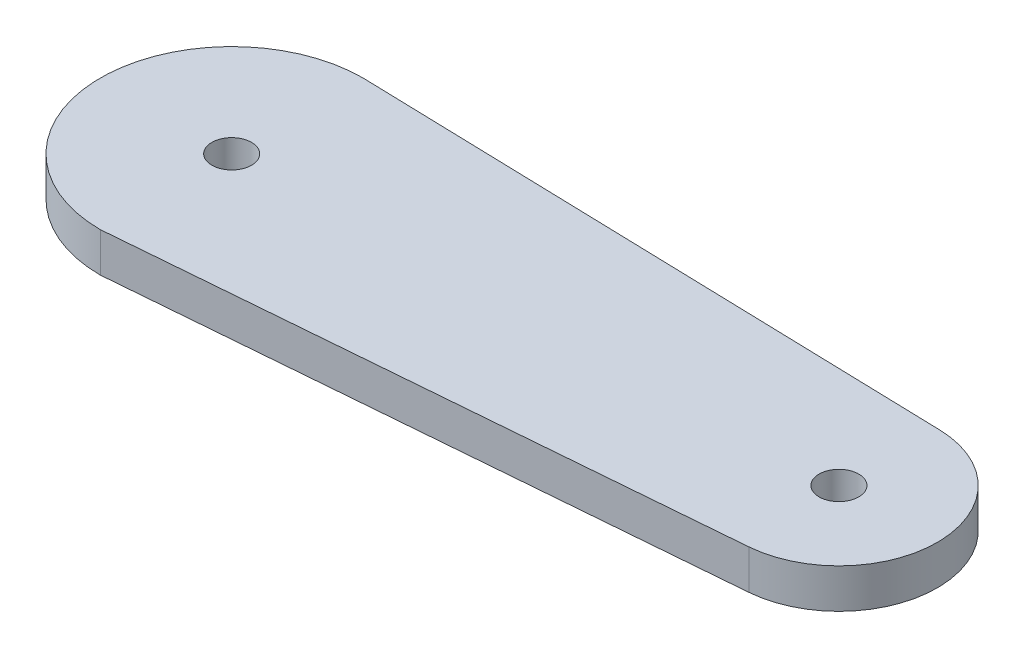
SolidWorks part; units mm, degrees
ref_plane "Front Plane" through (0, 0, 0) normal (0, 0, 1) x (1, 0, 0)
ref_plane "Top Plane" through (0, 0, 0) normal (0, 1, 0) x (1, 0, 0)
ref_plane "Right Plane" through (0, 0, 0) normal (1, 0, 0) x (0, 0, -1)
sketch "Sketch1" plane through (0, 0, 0) normal (0, 1, 0) x (1, 0, 0)
  line L0 (0, 10) -> (45.1912, 8.7436)
  line L1 (0, -10) -> (45.601, -6.2279)
  circle A0 centre (0, 0) radius 10
  circle A1 centre (44.9827, 1.2465) radius 7.5
  dimension "D2" = 20
  dimension "D3" = 15
  dimension "D1" = 45
extrude "Boss-Extrude1" add sketch "Sketch1" along normal blind 3 contours L1 A0 L0 | A1 L0 A0 L1 | A1 L1
sketch "Sketch2" plane through (0, 3, 0) normal (0, 1, 0) x (1, 0, 0)
  circle A0 centre (0, 0) radius 1.51
  circle A1 centre (44.9827, 1.2465) radius 1.51
  dimension "D1" = 3.02
  dimension "D2" = 3.02
extrude "Cut-Extrude1" cut sketch "Sketch2" against normal up to next
